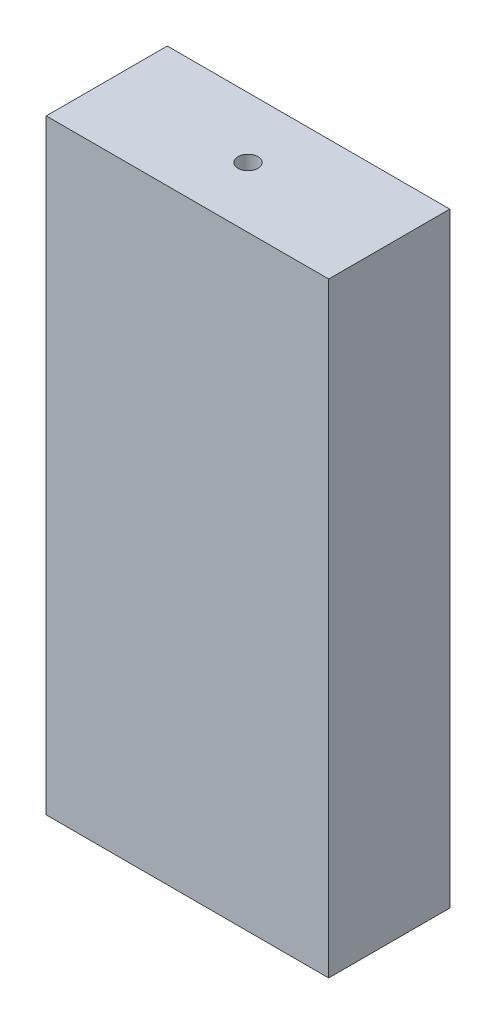
SolidWorks part; units mm, degrees
material "Balsa"
ref_plane "Front Plane" through (0, 0, 0) normal (0, 0, 1) x (1, 0, 0)
ref_plane "Top Plane" through (0, 0, 0) normal (0, 1, 0) x (1, 0, 0)
ref_plane "Right Plane" through (0, 0, 0) normal (1, 0, 0) x (0, 0, -1)
sketch "Sketch1" plane through (0, 0, 0) normal (0, 1, 0) x (1, 0, 0)
  line L1 (0, 0) -> (88.9, 0)
  line L2 (0, 0) -> (0, 38.1)
  line L3 (0, 38.1) -> (88.9, 38.1)
  line L4 (88.9, 0) -> (88.9, 38.1)
  circle A0 centre (44.45, 19.05) radius 3.175
  dimension "D3" = 6.35
  dimension "D4" = 44.45
  dimension "D5" = 19.05
  dimension "D1" = 38.1
  dimension "D2" = 88.9
extrude "Boss-Extrude1" add sketch "Sketch1" along normal blind 190.5
